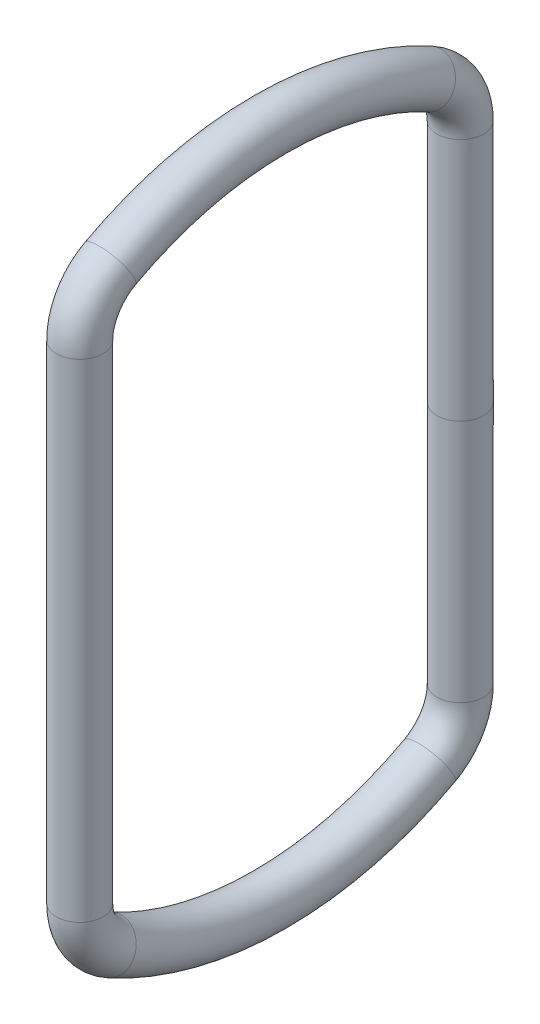
SolidWorks part; units mm, degrees
material "Copper"
ref_plane "Front Plane" through (0, 0, 0) normal (0, 0, 1) x (1, 0, 0)
ref_plane "Top Plane" through (0, 0, 0) normal (0, 1, 0) x (1, 0, 0)
ref_plane "Right Plane" through (0, 0, 0) normal (1, 0, 0) x (0, 0, -1)
sketch "Sketch1" plane through (0, 0, 0) normal (1, 0, 0) x (0, 0, -1)
  line L0 (2.76, 4.1779) -> (2.76, -4.1779) construction
  line L1 (-2.76, 4.1779) -> (-2.76, -4.1779) construction
  line L2 (2.76, 4.1779) -> (2.76, -4.1779)
  line L3 (-2.76, 4.1779) -> (-2.76, -4.1779)
  arc A0 (-2.4979, 4.6177) -> (2.4979, 4.6177) centre (0, 0) cw construction
  arc A1 (-2.4979, -4.6177) -> (2.4979, -4.6177) centre (0, 0) ccw construction
  arc A2 (2.76, -4.1779) -> (2.4979, -4.6177) centre (2.26, -4.1779) cw construction
  arc A3 (-2.76, -4.1779) -> (-2.4979, -4.6177) centre (-2.26, -4.1779) ccw construction
  arc A4 (2.4979, 4.6177) -> (2.76, 4.1779) centre (2.26, 4.1779) cw construction
  arc A5 (-2.76, 4.1779) -> (-2.4979, 4.6177) centre (-2.26, 4.1779) cw construction
  arc A6 (2.76, -4.1779) -> (2.4979, -4.6177) centre (2.26, -4.1779) cw
  arc A7 (-2.4979, -4.6177) -> (2.4979, -4.6177) centre (0, 0) ccw
  arc A8 (-2.76, -4.1779) -> (-2.4979, -4.6177) centre (-2.26, -4.1779) ccw
  arc A9 (-2.76, 4.1779) -> (-2.4979, 4.6177) centre (-2.26, 4.1779) cw
  arc A10 (-2.4979, 4.6177) -> (2.4979, 4.6177) centre (0, 0) cw
  arc A11 (2.4979, 4.6177) -> (2.76, 4.1779) centre (2.26, 4.1779) cw
  dimension "D1" = 0
sketch "Sketch2" plane through (0, 0, 0) normal (0, 1, 0) x (1, 0, 0)
  line L0 (0, 2.4979) -> (0, 2.76) construction
  circle A0 centre (0, 3.26) radius 0.4
  dimension "D1" = 0.8
sweep "Sweep1" add profiles "Sketch2" path "Sketch1"
